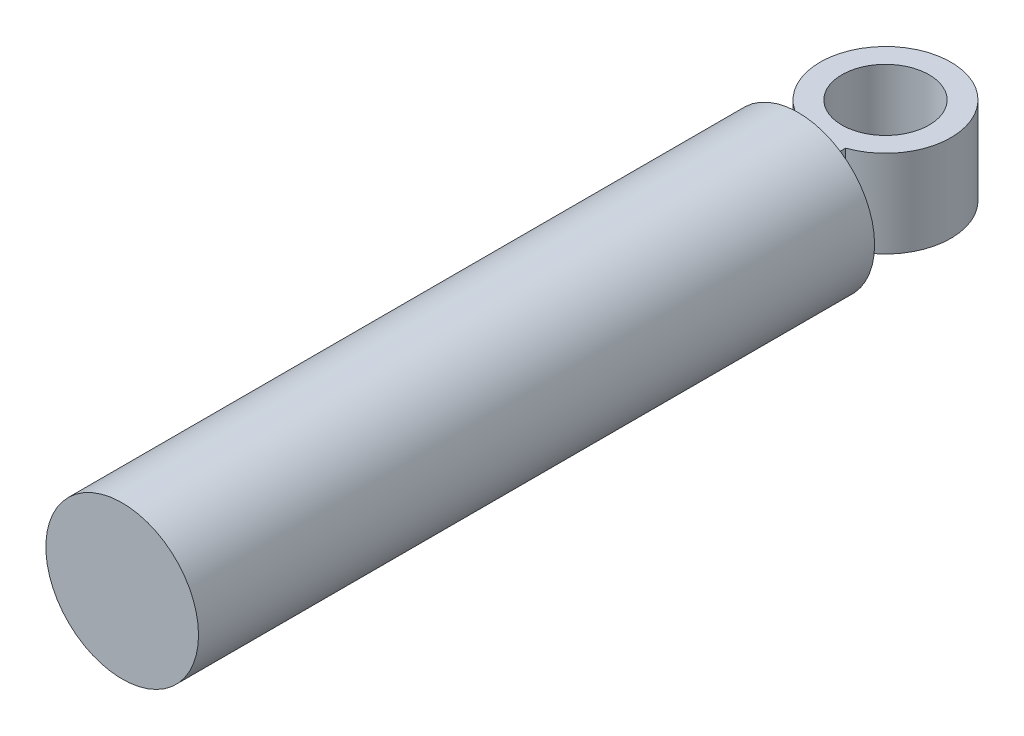
SolidWorks part; units mm, degrees
material "AISI 1020"
ref_plane "Ön Düzlem" through (0, 0, 0) normal (0, 0, 1) x (1, 0, 0)
ref_plane "Üst Düzlem" through (0, 0, 0) normal (0, 1, 0) x (1, 0, 0)
ref_plane "Sağ Düzlem" through (0, 0, 0) normal (1, 0, 0) x (0, 0, -1)
sketch "Çizim1" plane through (0, 0, 0) normal (0, 0, 1) x (1, 0, 0)
  circle A0 centre (0, 0) radius 35
  dimension "D1" = 70
extrude "Yükseklik-Ekstrüzyon1" add sketch "Çizim1" along normal blind 310
sketch "Çizim2" plane through (0, 0, 0) normal (0, 1, 0) x (1, 0, 0)
  line L0 (0, 0) -> (0, 40) construction
  line L1 (-10, 0) -> (-10, 11.7157)
  line L2 (10, 0) -> (10, 11.7157)
  line L3 (-10, 0) -> (-10, 40) construction
  line L4 (10, 0) -> (10, 40) construction
  line L5 (-10, 0) -> (10, 0)
  arc A0 (10, 11.7157) -> (-10, 11.7157) centre (0, 40) ccw
  circle A1 centre (0, 40) radius 20
  dimension "D2" = 60
  dimension "D3" = 40
  dimension "D1" = 40
  dimension "D4" = 10
  dimension "D5" = 10
extrude "Yükseklik-Ekstrüzyon2" add sketch "Çizim2" along normal mid plane 40
